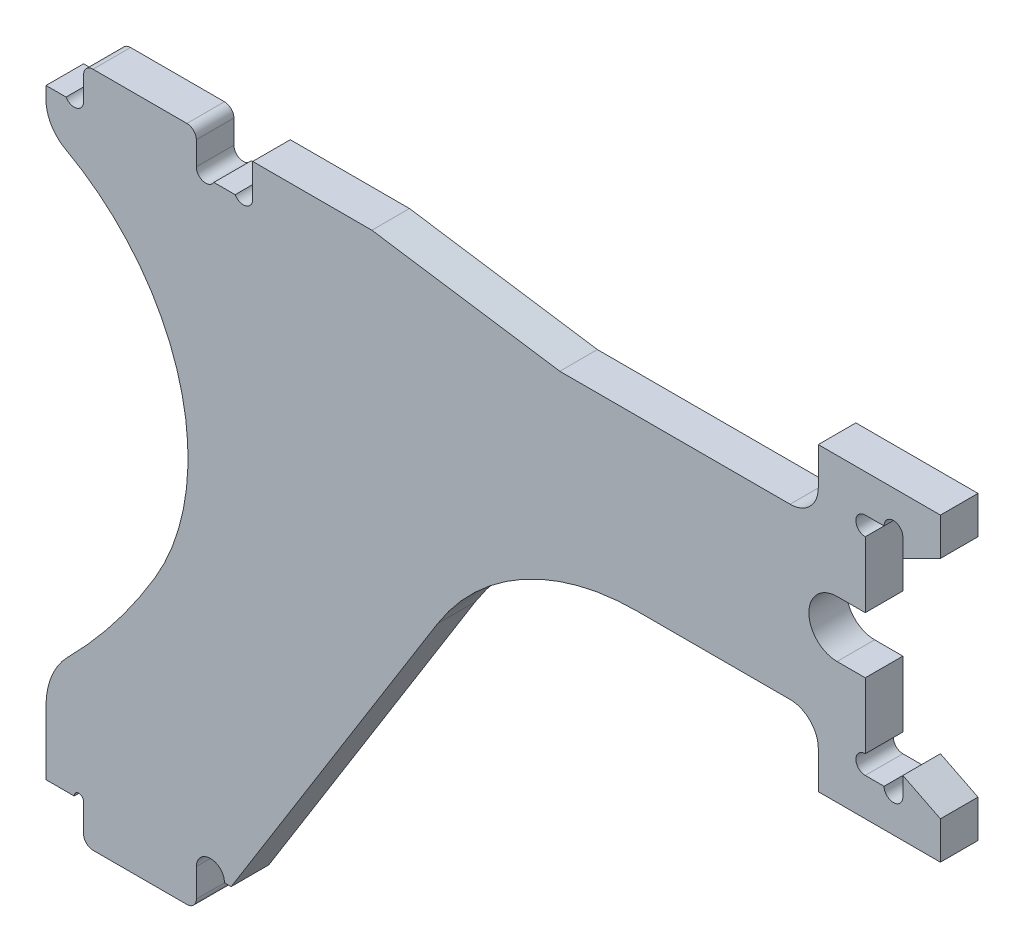
SolidWorks part; units mm, degrees
material "ABS"
ref_plane "Front Plane" through (0, 0, 0) normal (0, 0, 1) x (1, 0, 0)
ref_plane "Top Plane" through (0, 0, 0) normal (0, 1, 0) x (1, 0, 0)
ref_plane "Right Plane" through (0, 0, 0) normal (1, 0, 0) x (0, 0, -1)
sketch "Sketch4" plane through (0, 0, 0) normal (0, 0, 1) x (1, 0, 0)
  line L0 (-13.0509, 16) -> (-6.7065, 16)
  line L1 (-6.7065, 16) -> (3.2935, 14.5)
  line L2 (3.2935, 14.5) -> (17.0509, 14.5)
  line L3 (17.0509, 14.5) -> (17.0509, 18)
  line L4 (17.0509, 18) -> (23.5509, 18)
  line L5 (23.5509, 18) -> (23.5509, 16)
  line L6 (23.5509, 16) -> (21.5509, 15)
  line L7 (21.5509, 15) -> (21.5509, 16)
  line L8 (20.5509, 16) -> (19.5509, 16)
  line L9 (19.5509, 15) -> (19.5509, 11.5)
  line L10 (19.5509, 11.5) -> (18.0509, 11.5)
  line L11 (18.0509, 8.5) -> (19.5509, 8.5)
  line L12 (19.5509, 8.5) -> (19.5509, 5)
  line L13 (19.5509, 4) -> (20.5509, 4)
  line L14 (21.5509, 4) -> (21.5509, 5)
  line L15 (23.5509, 4) -> (21.5509, 5)
  line L16 (23.5509, 4) -> (23.5509, 2)
  line L17 (23.5509, 2) -> (17.0509, 2)
  line L18 (17.0509, 2) -> (17.0509, 5.5)
  line L19 (17.0509, 5.5) -> (7.3947, 5.5)
  line L20 (-3.212, -0.3857) -> (-14.1963, -18)
  line L21 (-14.1963, -18) -> (-14.5509, -18)
  line L22 (-16.0509, -18) -> (-16.0509, -19.5)
  line L23 (-16.5509, -20) -> (-21.5509, -20)
  line L24 (-22.0509, -19.5) -> (-22.0509, -18)
  line L25 (-22.5509, -18) -> (-24.0509, -18)
  line L26 (-24.0509, -18) -> (-24.0509, -14.5882)
  line L27 (-24.0509, 13.3353) -> (-24.0509, 14)
  line L28 (-24.0509, 14) -> (-22.9839, 14)
  line L29 (-22.0509, 14.25) -> (-22.0509, 15.5)
  line L30 (-21.5509, 16) -> (-16.5509, 16)
  line L31 (-16.0509, 15.5) -> (-16.0509, 14.25)
  line L32 (-15.1179, 14) -> (-13.9839, 14)
  line L33 (-13.0509, 14.25) -> (-13.0509, 16)
  line L34 (55, 0) -> (-55, 0) construction
  line L35 (18.0509, 10) -> (6.724, 10) construction
  line L36 (20.5509, 16) -> (20.5509, 4) construction
  arc A0 (-22.0509, 15.5) -> (-21.5509, 16) centre (-21.5509, 15.5) cw
  arc A1 (-16.5509, 16) -> (-16.0509, 15.5) centre (-16.5509, 15.5) cw
  arc A2 (-16.0509, 14.25) -> (-15.1179, 14) centre (-15.5509, 14.25) ccw
  arc A3 (-13.0509, 14.25) -> (-13.9839, 14) centre (-13.5509, 14.25) cw
  arc A4 (-22.0509, 14.25) -> (-22.9839, 14) centre (-22.5509, 14.25) cw
  arc A5 (19.5509, 16) -> (19.5509, 15) centre (19.5509, 15.5) ccw
  arc A6 (21.5509, 16) -> (20.5509, 16) centre (21.0509, 16) ccw
  arc A7 (18.0509, 11.5) -> (18.0509, 8.5) centre (18.0509, 10) ccw
  arc A8 (19.5509, 4) -> (19.5509, 5) centre (19.5509, 4.5) cw
  arc A9 (21.5509, 4) -> (20.5509, 4) centre (21.0509, 4) cw
  arc A10 (-3.212, -0.3857) -> (7.3947, 5.5) centre (7.3947, -7) cw
  arc A11 (-16.0509, -18) -> (-14.5509, -18) centre (-15.3009, -18) cw
  arc A12 (-22.0509, -18) -> (-22.5509, -18) centre (-22.3009, -18) ccw
  arc A13 (-22.0509, -19.5) -> (-21.5509, -20) centre (-21.5509, -19.5) ccw
  arc A14 (-16.5509, -20) -> (-16.0509, -19.5) centre (-16.5509, -19.5) ccw
  arc A15 (-24.0509, 13.3353) -> (-23.0082, 11.5793) centre (-22.0509, 13.3353) ccw
  arc A16 (-23.0082, 11.5793) -> (-18.2572, -5.8009) centre (-28.9915, 0.6043) cw
  arc A17 (-18.2572, -5.8009) -> (-22.8892, -11.7696) centre (-44.9211, 10.1096) cw
  arc A18 (-22.8892, -11.7696) -> (-24.0509, -14.5882) centre (-20.0509, -14.5882) ccw
  point P72 (19.5509, 13.25)
  point P73 (18.8009, 11.5)
  point P76 (20.5509, 10)
  dimension "D10" = 0.5
  dimension "D1" = 41.6018
  dimension "D2" = 2
  dimension "D3" = 6
  dimension "D4" = 2
  dimension "D5" = 3
  dimension "D6" = 2
  dimension "D7" = 2
  dimension "D8" = 32
  dimension "D9" = 3
  dimension "D11" = 58.052
  dimension "D12" = 22.7629
  dimension "D13" = 12
  dimension "D14" = 2
  dimension "D15" = 2
  dimension "D16" = 3
  dimension "D17" = 3.5
  dimension "D18" = 3.5
  dimension "D19" = 3
extrude "Boss-Extrude1" add sketch "Sketch4" along normal blind 2
fillet "Fillet1" radius 1.5 2 edges at (17.0509, 14.5, 1) (17.0509, 5.5, 1)
